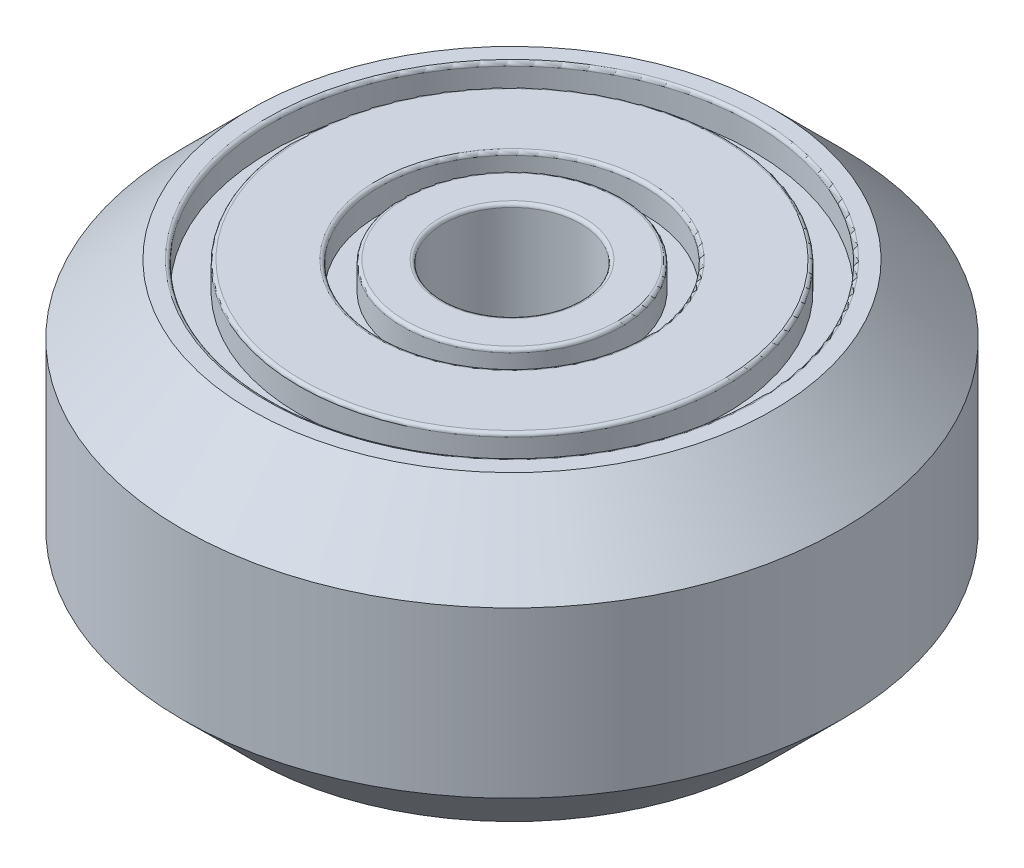
SolidWorks part; units mm, degrees
ref_plane "Front Plane" through (0, 0, 0) normal (0, 0, 1) x (1, 0, 0)
ref_plane "Top Plane" through (0, 0, 0) normal (0, 1, 0) x (1, 0, 0)
ref_plane "Right Plane" through (0, 0, 0) normal (1, 0, 0) x (0, 0, -1)
sketch "Sketch1" plane through (0, 0, 0) normal (0, 1, 0) x (1, 0, 0)
  circle A0 centre (0, 0) radius 12
  circle A1 centre (0, 0) radius 2.5
  dimension "D1" = 24
  dimension "D2" = 5
extrude "Boss-Extrude1" add sketch "Sketch1" along normal blind 11
sketch "Sketch3" plane through (0, 11, 0) normal (0, 1, 0) x (1, 0, 0)
  circle A0 centre (0, 0) radius 8.7957
  circle A1 centre (0, 0) radius 7.7455
  circle A2 centre (0, 0) radius 4.8221
  circle A3 centre (0, 0) radius 3.9908
extrude "Cut-Extrude1" cut sketch "Sketch3" against normal blind 1 contours A0 A1 | A2 A3
ref_plane "Plane1" through (0, 5.5, 0) normal (0, 1, 0) x (1, 0, 0)
chamfer "Chamfer1" distance 2.5 angle 45 2 edges at (0, 11, 12) (0, 0, 12)
fillet "Fillet2" radius 0.125 5 edges at (0, 11, 8.7957) (0, 11, 2.5) (0, 11, 3.9908) (0, 11, 4.8221) (0, 11, 7.7455)
mirror "Mirror3" about plane through (0, 5.5, 0) normal (0, 1, 0) of "Cut-Extrude1"
move or copy body "Body-Move/Copy1" bodies to move or copy 106
